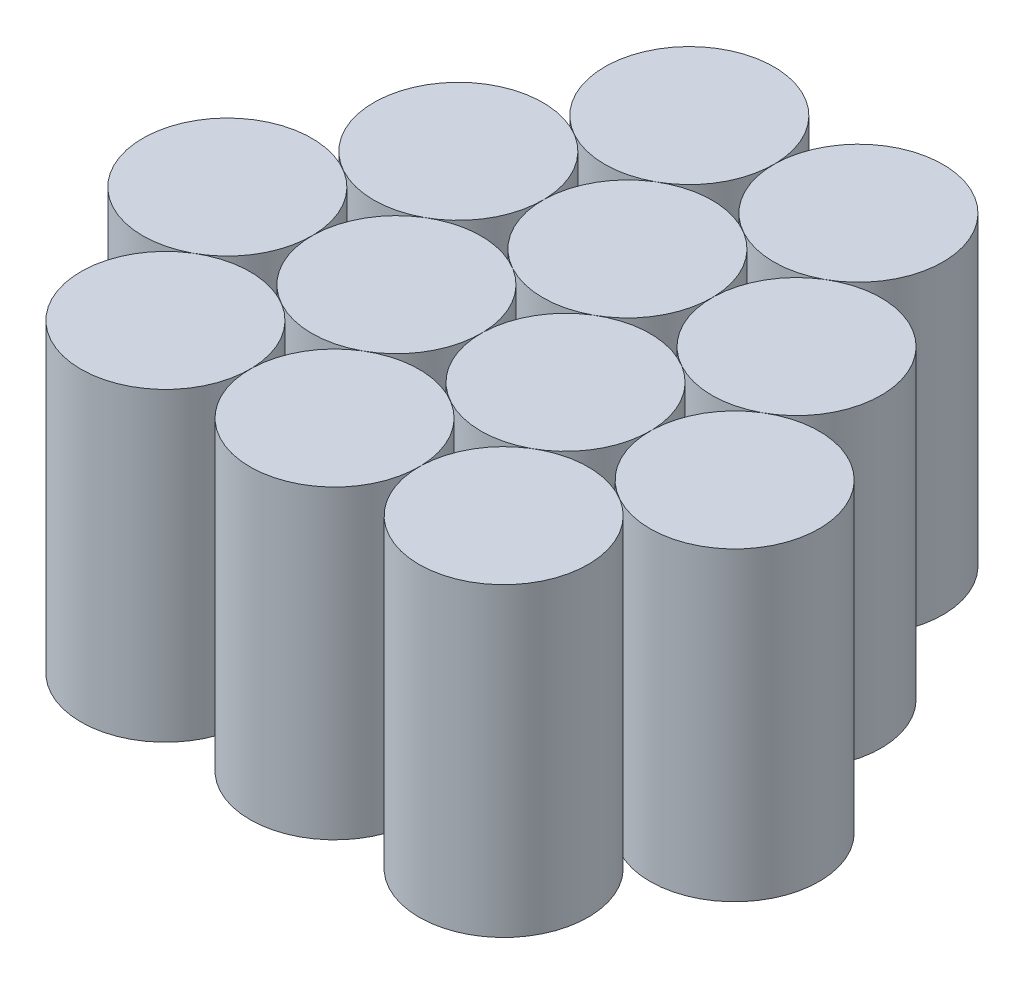
SolidWorks part; units mm, degrees
ref_plane "Front Plane" through (0, 0, 0) normal (0, 0, 1) x (1, 0, 0)
ref_plane "Top Plane" through (0, 0, 0) normal (0, 1, 0) x (1, 0, 0)
ref_plane "Right Plane" through (0, 0, 0) normal (1, 0, 0) x (0, 0, -1)
sketch "Sketch1" plane through (0, 0, 0) normal (0, 1, 0) x (1, 0, 0)
  line L0 (0, 19.6507) -> (-17.018, -9.8253) construction
  line L1 (-17.018, -9.8253) -> (17.018, -9.8253) construction
  line L2 (17.018, -9.8253) -> (0, 19.6507) construction
  line L3 (-8.509, 4.9127) -> (0, 0) construction
  line L4 (0, 0) -> (0, 19.6507) construction
  circle A0 centre (-17.018, -9.8253) radius 17.018
  circle A1 centre (17.018, -9.8253) radius 17.018
  circle A2 centre (0, 19.6507) radius 17.018
  circle A3 centre (17.018, 49.1267) radius 17.018
  circle A4 centre (0, -39.3014) radius 17.018
  circle A5 centre (-51.054, -9.8253) radius 17.018
  circle A6 centre (-34.036, 19.6507) radius 17.018
  circle A7 centre (51.054, -9.8253) radius 17.018
  circle A8 centre (-34.036, -39.3014) radius 17.018
  circle A9 centre (34.036, -39.3014) radius 17.018
  circle A10 centre (34.036, 19.6507) radius 17.018
  circle A11 centre (-17.018, 49.1267) radius 17.018
  point P25 (0, 0)
  dimension "D1" = 34.036
  dimension "D2" = 34.036
  dimension "D3" = 34.036
  dimension "D4" = 34.036
  dimension "D5" = 34.036
  dimension "D6" = 34.036
  dimension "D7" = 34.036
  dimension "D8" = 34.036
  dimension "D9" = 34.036
  dimension "D10" = 34.036
  dimension "D11" = 34.036
  dimension "D12" = 34.036
extrude "Boss-Extrude1" add sketch "Sketch1" along normal blind 61.5 contours A9 | A7 | A10 | A3 | A11 | A6 | A2 | A0 | A5 | A8 | A4 | A1
equation "\"D2@Sketch1\"=\"D1@Sketch1\""
equation "\"D3@Sketch1\"=\"D1@Sketch1\""
equation "\"D4@Sketch1\"=\"D1@Sketch1\""
equation "\"D5@Sketch1\"=\"D1@Sketch1\""
equation "\"D6@Sketch1\"=\"D1@Sketch1\""
equation "\"D7@Sketch1\"=\"D1@Sketch1\""
equation "\"D8@Sketch1\"=\"D1@Sketch1\""
equation "\"D9@Sketch1\"=\"D1@Sketch1\""
equation "\"D10@Sketch1\"=\"D1@Sketch1\""
equation "\"D11@Sketch1\"=\"D1@Sketch1\""
equation "\"D12@Sketch1\"=\"D1@Sketch1\""
